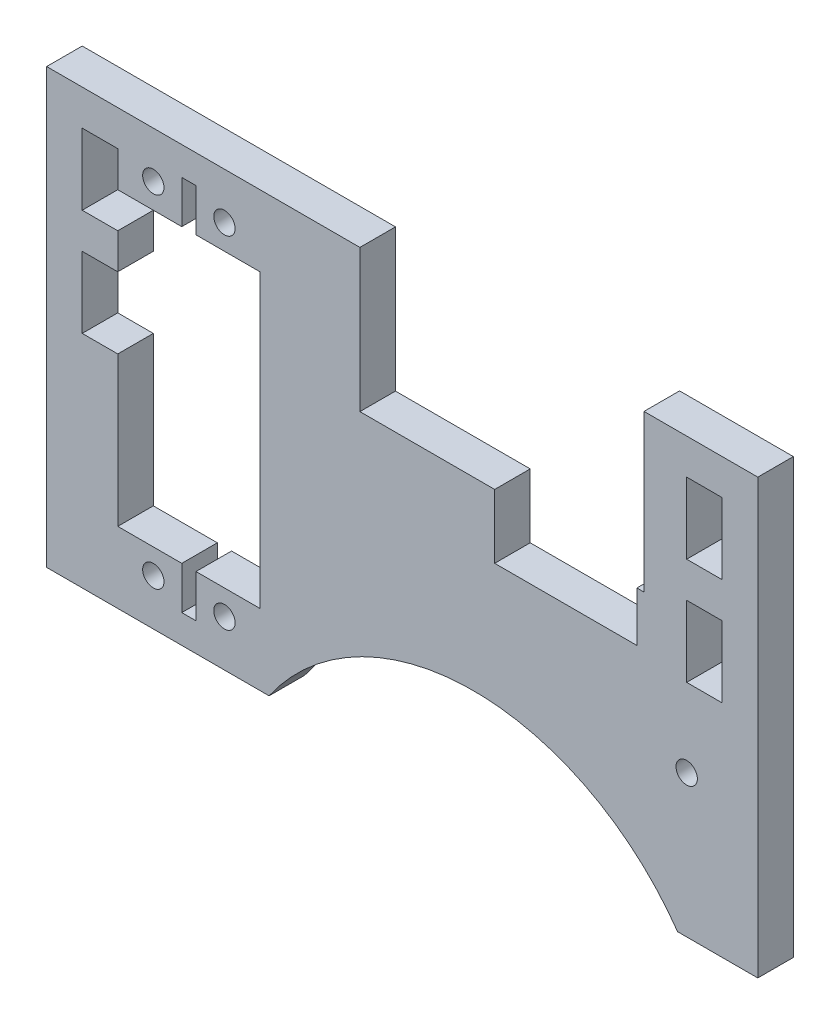
SolidWorks part; units mm, degrees
ref_plane "Plan de face" through (0, 0, 0) normal (0, 0, 1) x (1, 0, 0)
ref_plane "Plan de dessus" through (0, 0, 0) normal (0, 1, 0) x (1, 0, 0)
ref_plane "Plan de droite" through (0, 0, 0) normal (1, 0, 0) x (0, 0, -1)
sketch "Esquisse1" plane through (0, 0, 0) normal (0, 0, 1) x (1, 0, 0)
  line L0 (20, 71) -> (20, 0) construction
  line L1 (0, 0) -> (31.2772, 0)
  line L2 (0, 0) -> (0, 61)
  line L3 (0, 61) -> (44.05, 61)
  line L4 (100, 0) -> (100, 61)
  line L5 (10, 30.5) -> (30, 30.5) construction
  line L6 (10, 51) -> (19, 51)
  line L7 (10, 46) -> (10, 41)
  line L8 (10, 10) -> (19, 10)
  line L9 (30, 51) -> (30, 10)
  line L10 (20, 20) -> (90, 20) construction
  line L11 (88.7228, 0) -> (100, 0)
  line L12 (21, 4) -> (21, 10)
  line L13 (19, 57) -> (21, 57)
  line L14 (19, 57) -> (19, 51)
  line L15 (21, 10) -> (30, 10)
  line L16 (21, 57) -> (21, 51)
  line L17 (19, 4) -> (21, 4)
  line L18 (19, 4) -> (19, 10)
  line L19 (21, 51) -> (30, 51)
  line L20 (10, 31) -> (10, 10)
  line L21 (90, 56) -> (95, 56)
  line L22 (90, 56) -> (90, 46)
  line L23 (90, 46) -> (95, 46)
  line L24 (95, 56) -> (95, 46)
  line L25 (90, 41) -> (95, 41)
  line L26 (90, 41) -> (90, 31)
  line L27 (90, 31) -> (95, 31)
  line L28 (95, 41) -> (95, 31)
  line L29 (5, 56) -> (10, 56)
  line L30 (5, 56) -> (5, 46)
  line L31 (5, 46) -> (10, 46)
  line L32 (10, 56) -> (10, 51)
  line L33 (5, 41) -> (10, 41)
  line L34 (5, 41) -> (5, 31)
  line L35 (5, 31) -> (10, 31)
  line L36 (84, 61) -> (100, 61)
  line L37 (63, 41) -> (44.05, 41)
  line L38 (84, 61) -> (84, 39)
  line L39 (84, 39) -> (83, 39)
  line L40 (44.05, 61) -> (44.05, 41)
  line L42 (83, 39) -> (83, 32)
  line L43 (83, 32) -> (63, 32)
  line L44 (63, 41) -> (63, 32)
  circle A0 centre (15, 6.5) radius 1.5
  circle A1 centre (25, 6.5) radius 1.5
  circle A2 centre (25, 54.5) radius 1.5
  circle A3 centre (15, 54.5) radius 1.5
  circle A4 centre (20, 20) radius 1.5 construction
  circle A5 centre (20, 20) radius 1.5 construction
  circle A6 centre (90, 20) radius 1.5
  circle A7 centre (60, -20) radius 35 construction
  arc A8 (31.2772, 0) -> (88.7228, 0) centre (60, -20) cw
  dimension "D6" = 3.5
  dimension "D8" = 3
  dimension "D9" = 3
  dimension "D10" = 70
  dimension "D13" = 70
  dimension "D16" = 2
  dimension "D1" = 10
  dimension "D2" = 41
  dimension "D3" = 20
  dimension "D4" = 10
  dimension "D5" = 100
  dimension "D7" = 5
  dimension "D11" = 10
  dimension "D12" = 10
  dimension "D14" = 40
  dimension "D15" = 40
  dimension "D17" = 6
  dimension "D18" = 5
  dimension "D19" = 5
  dimension "D20" = 10
  dimension "D21" = 5
  dimension "D22" = 5
  dimension "D23" = 5
  dimension "D24" = 10
  dimension "D25" = 6
  dimension "D26" = 20
  dimension "D27" = 40
  dimension "D28" = 1
  dimension "D29" = 20
  dimension "D30" = 9
  dimension "D31" = 22
  dimension "D32" = 7
extrude "Boss.-Extru.1" add sketch "Esquisse1" along normal blind 5
